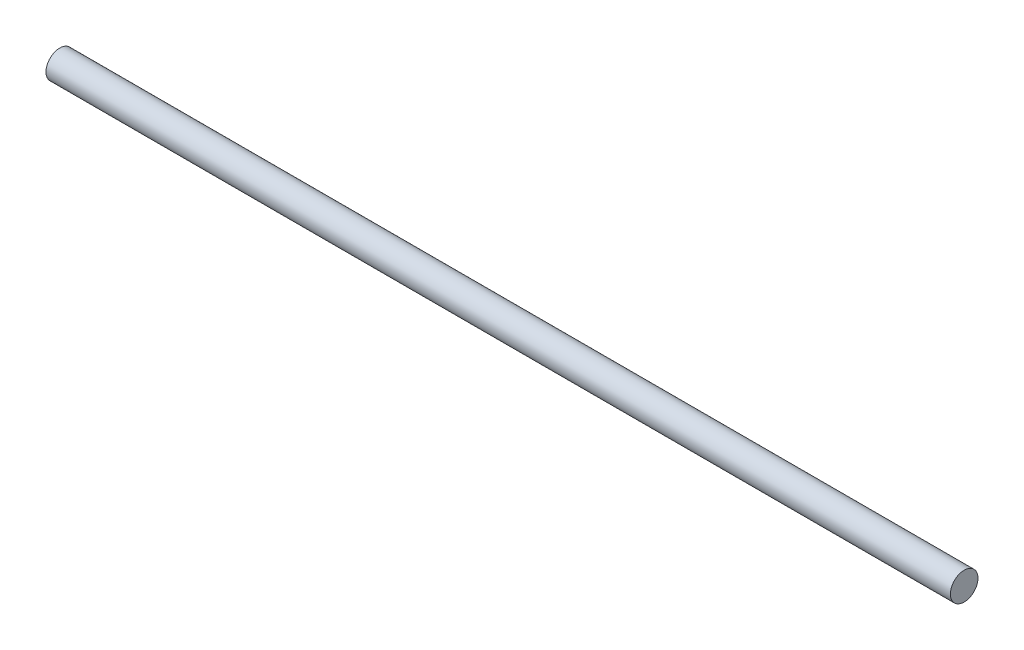
SolidWorks part; units mm, degrees
ref_plane "Front" through (0, 0, 0) normal (0, 0, 1) x (1, 0, 0)
ref_plane "Top" through (0, 0, 0) normal (0, 1, 0) x (1, 0, 0)
ref_plane "Right" through (0, 0, 0) normal (1, 0, 0) x (0, 0, -1)
sketch "Sketch2" plane through (0, 0, 0) normal (1, 0, 0) x (0, 0, -1)
  circle A0 centre (0, 0) radius 1.6
  dimension "D1" = 3.2
extrude "Base-Extrude" add sketch "Sketch2" along normal blind 104.775
